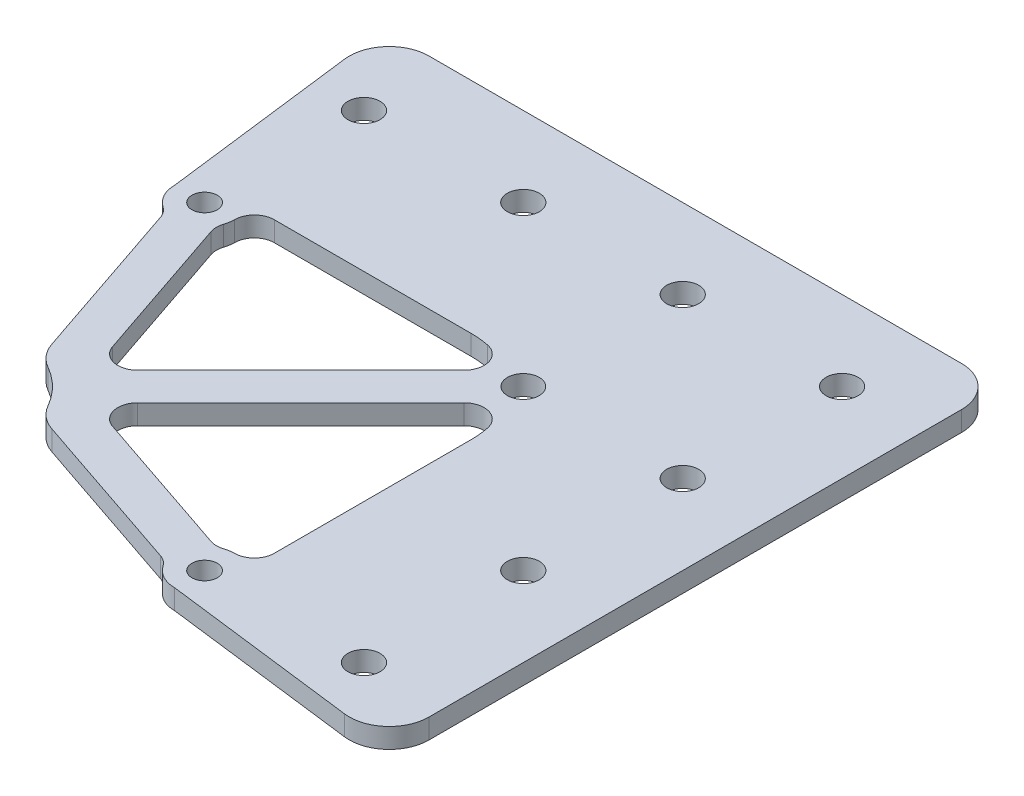
SolidWorks part; units mm, degrees
ref_plane "Front" through (0, 0, 0) normal (0, 0, 1) x (1, 0, 0)
ref_plane "Top" through (0, 0, 0) normal (0, 1, 0) x (1, 0, 0)
ref_plane "Right" through (0, 0, 0) normal (1, 0, 0) x (0, 0, -1)
sketch "Sketch1" plane through (0, 0, 0) normal (0, 1, 0) x (1, 0, 0)
  line L1 (-63.5, 63.5) -> (63.5, 63.5)
  line L2 (-63.5, 63.5) -> (-63.5, -63.5)
  line L3 (-63.5, -63.5) -> (63.5, -63.5)
  line L4 (63.5, 63.5) -> (63.5, -63.5)
  point P4 (39.9494, -25.0788)
  point P5 (0, 63.5)
  point P7 (-63.5, 0)
  point P8 (-38.1, 27.9109)
  dimension "D1" = 127
  dimension "D2" = 127
extrude "Boss-Extrude 1" add sketch "Sketch1" along normal blind 3.175
sketch "Sketch5" plane through (0, 0, 0) normal (0, -1, 0) x (1, 0, 0)
  line L0 (-30.1625, -25.4) -> (-34.925, -63.5)
  line L8 (-34.925, -63.5) -> (-63.5, -63.5)
  line L11 (-63.5, -63.5) -> (-63.5, 63.5)
  line L23 (25.4, 30.1625) -> (63.5, 34.925)
  line L27 (-38.3869, -28.575) -> (-33.3375, -28.575)
  line L28 (-26.8812, -19.8711) -> (-20.4899, -0.9811)
  line L29 (-34.3097, 4.4018) -> (-36.3512, 2.183)
  line L31 (-26.8812, -19.8711) -> (-20.4899, -0.9811)
  line L59 (-63.5, 63.5) -> (63.5, 63.5)
  line L64 (63.5, 63.5) -> (63.5, 34.925)
  line L73 (18.4349, -22.9251) -> (-7.5737, 3.0836)
  line L74 (-12.8263, 1.8561) -> (-20.8661, -21.9063)
  line L75 (-17.4625, -28.575) -> (13.9023, -28.575)
  line L76 (18.4349, -22.9251) -> (-7.5737, 3.0836)
  line L77 (-12.8263, 1.8561) -> (-20.8661, -21.9063)
  line L78 (-17.4625, -28.575) -> (13.9023, -28.575)
  line L88 (63.5, 63.5) -> (63.5, -63.5) construction
  line L89 (63.5, -63.5) -> (-63.5, -63.5) construction
  line L109 (28.575, -13.9023) -> (28.575, 17.4625)
  line L110 (21.9063, 20.8661) -> (-1.8561, 12.8263)
  line L111 (-3.0836, 7.5737) -> (22.9251, -18.4349)
  line L112 (28.575, -13.9023) -> (28.575, 17.4625)
  line L113 (21.9063, 20.8661) -> (-1.8561, 12.8263)
  line L114 (-3.0836, 7.5737) -> (22.9251, -18.4349)
  line L116 (0.9811, 20.4899) -> (19.8711, 26.8812)
  line L117 (28.575, 33.3375) -> (28.575, 44.3244)
  line L118 (25.4, 47.4994) -> (13.9965, 47.4994)
  line L119 (-1.9502, 36.2794) -> (-4.2984, 34.1559)
  line L120 (0.9811, 20.4899) -> (19.8711, 26.8812)
  line L126 (-20.4899, -0.9811) -> (-17.1581, 8.8661)
  line L127 (0.9811, 20.4899) -> (-8.8661, 17.1581)
  arc A69 (-41.0199, -7.9307) -> (-43.8396, -12.1698) centre (-40.8498, -11.1011) ccw
  arc A70 (-43.3218, -21.0917) -> (-43.8396, -12.1698) centre (-58.7883, -17.5133) ccw
  arc A71 (-43.3218, -21.0917) -> (-42.5927, -23.9267) centre (-40.2285, -21.8074) ccw
  arc A72 (-41.4877, -26.0822) -> (-42.5927, -23.9267) centre (-46.139, -27.1056) ccw
  arc A73 (-41.4877, -26.0822) -> (-38.3869, -28.575) centre (-38.3869, -25.4) ccw
  arc A74 (-33.3375, -28.575) -> (-30.1625, -25.4) centre (-33.3375, -25.4) ccw
  arc A75 (-28.0932, -21.4721) -> (-30.1625, -25.4) centre (-25.4, -25.4) ccw
  arc A76 (-28.0932, -21.4721) -> (-26.8812, -19.8711) centre (-29.8887, -18.8536) ccw
  arc A77 (-20.4899, -0.9811) -> (-23.3156, 3.2062) centre (-23.4974, 0.0365) ccw
  arc A78 (-30.5807, 5.1053) -> (-23.3156, 3.2062) centre (-22.225, 22.225) ccw
  arc A79 (-30.5807, 5.1053) -> (-34.3097, 4.4018) centre (-31.9733, 2.252) ccw
  arc A80 (-36.3512, 2.183) -> (-36.9188, -1.2501) centre (-34.0147, 0.0332) ccw
  arc A81 (-41.0199, -7.9307) -> (-36.9188, -1.2501) centre (-41.275, -3.175) ccw
  arc A88 (-28.0932, -21.4721) -> (-30.1625, -25.4) centre (-25.4, -25.4) ccw
  arc A89 (-28.0932, -21.4721) -> (-26.8812, -19.8711) centre (-29.8887, -18.8536) ccw
  arc A274 (25.4, -23.3807) -> (25.4, -27.4193) centre (25.4, -25.4) ccw
  arc A275 (25.4, -27.4193) -> (25.4, -23.3807) centre (25.4, -25.4) ccw
  arc A276 (25.4, -23.3807) -> (25.4, -27.4193) centre (25.4, -25.4) ccw construction
  arc A277 (25.4, -27.4193) -> (25.4, -23.3807) centre (25.4, -25.4) ccw construction
  arc A298 (-22.225, 7.9375) -> (-22.225, 36.5125) centre (-22.225, 22.225) ccw
  arc A299 (-22.225, 36.5125) -> (-22.225, 7.9375) centre (-22.225, 22.225) ccw
  arc A300 (-17.1581, 8.8661) -> (-8.8661, 17.1581) centre (-22.225, 22.225) ccw
  arc A313 (-25.4, -23.3807) -> (-25.4, -27.4193) centre (-25.4, -25.4) ccw construction
  arc A314 (25.4, 27.4193) -> (25.4, 23.3807) centre (25.4, 25.4) ccw construction
  arc A315 (13.9023, -28.575) -> (16.8216, -28.2817) centre (13.9023, -13.9023) ccw
  arc A316 (16.8216, -28.2817) -> (18.4349, -22.9251) centre (16.1899, -25.1701) ccw
  arc A317 (-7.5737, 3.0836) -> (-9.8188, 4.0135) centre (-9.8188, 0.8385) ccw
  arc A318 (-9.8188, 4.0135) -> (-12.8263, 1.8561) centre (-9.8188, 0.8385) ccw
  arc A319 (-20.8661, -21.9063) -> (-20.8752, -23.9143) centre (-17.8586, -22.9239) ccw
  arc A320 (-20.6375, -25.4) -> (-20.8752, -23.9143) centre (-25.4, -25.4) ccw
  arc A321 (-20.6375, -25.4) -> (-17.4625, -28.575) centre (-17.4625, -25.4) ccw
  arc A322 (13.9023, -28.575) -> (16.8216, -28.2817) centre (13.9023, -13.9023) ccw
  arc A323 (16.8216, -28.2817) -> (18.4349, -22.9251) centre (16.1899, -25.1701) ccw
  arc A324 (-7.5737, 3.0836) -> (-9.8188, 4.0135) centre (-9.8188, 0.8385) ccw
  arc A325 (-9.8188, 4.0135) -> (-12.8263, 1.8561) centre (-9.8188, 0.8385) ccw
  arc A326 (-20.8661, -21.9063) -> (-20.8752, -23.9143) centre (-17.8586, -22.9239) ccw
  arc A327 (-20.6375, -25.4) -> (-20.8752, -23.9143) centre (-25.4, -25.4) ccw
  arc A328 (-20.6375, -25.4) -> (-17.4625, -28.575) centre (-17.4625, -25.4) ccw
  arc A329 (28.2817, -16.8216) -> (28.575, -13.9023) centre (13.9023, -13.9023) ccw
  arc A330 (28.575, 17.4625) -> (25.4, 20.6375) centre (25.4, 17.4625) ccw
  arc A331 (23.9143, 20.8752) -> (25.4, 20.6375) centre (25.4, 25.4) ccw
  arc A332 (23.9143, 20.8752) -> (21.9063, 20.8661) centre (22.9239, 17.8586) ccw
  arc A333 (-1.8561, 12.8263) -> (-3.0836, 7.5737) centre (-0.8385, 9.8188) ccw
  arc A454 (22.9251, -18.4349) -> (25.1701, -19.3649) centre (25.1701, -16.1899) ccw
  arc A455 (25.1701, -19.3649) -> (28.2817, -16.8216) centre (25.1701, -16.1899) ccw
  arc A456 (28.2817, -16.8216) -> (28.575, -13.9023) centre (13.9023, -13.9023) ccw
  arc A457 (28.575, 17.4625) -> (25.4, 20.6375) centre (25.4, 17.4625) ccw
  arc A458 (23.9143, 20.8752) -> (25.4, 20.6375) centre (25.4, 25.4) ccw
  arc A459 (23.9143, 20.8752) -> (21.9063, 20.8661) centre (22.9239, 17.8586) ccw
  arc A460 (-1.8561, 12.8263) -> (-3.0836, 7.5737) centre (-0.8385, 9.8188) ccw
  arc A461 (22.9251, -18.4349) -> (25.1701, -19.3649) centre (25.1701, -16.1899) ccw
  arc A462 (25.1701, -19.3649) -> (28.2817, -16.8216) centre (25.1701, -16.1899) ccw
  arc A470 (19.8711, 26.8812) -> (21.4721, 28.0932) centre (18.8536, 29.8887) ccw
  arc A471 (25.4, 30.1625) -> (21.4721, 28.0932) centre (25.4, 25.4) ccw
  arc A472 (25.4, 30.1625) -> (28.575, 33.3375) centre (25.4, 33.3375) ccw
  arc A473 (28.575, 44.3244) -> (25.4, 47.4994) centre (25.4, 44.3244) ccw
  arc A474 (13.9965, 47.4994) -> (12.0915, 46.8644) centre (13.9965, 44.3244) ccw
  arc A475 (10.2574, 46.0231) -> (12.0915, 46.8644) centre (9.234, 50.6744) ccw
  arc A476 (10.2574, 46.0231) -> (7.8338, 42.2634) centre (10.9397, 42.9223) ccw
  arc A477 (3.175, 36.5125) -> (7.8338, 42.2634) centre (3.175, 41.275) ccw
  arc A478 (1.3776, 36.8647) -> (3.175, 36.5125) centre (3.175, 41.275) ccw
  arc A479 (1.3776, 36.8647) -> (-1.9502, 36.2794) centre (0.1793, 33.9245) ccw
  arc A480 (-4.2984, 34.1559) -> (-5.034, 30.433) centre (-2.1688, 31.801) ccw
  arc A481 (-3.2062, 23.3156) -> (-5.034, 30.433) centre (-22.225, 22.225) ccw
  arc A482 (-3.2062, 23.3156) -> (-0.0365, 20.3224) centre (-0.0365, 23.4974) ccw
  arc A483 (-0.0365, 20.3224) -> (0.9811, 20.4899) centre (-0.0365, 23.4974) ccw
  arc A484 (19.8711, 26.8812) -> (21.4721, 28.0932) centre (18.8536, 29.8887) ccw
  arc A485 (25.4, 30.1625) -> (21.4721, 28.0932) centre (25.4, 25.4) ccw
  arc A555 (-25.4, -23.3807) -> (-25.4, -27.4193) centre (-25.4, -25.4) ccw
  arc A556 (25.4, 27.4193) -> (25.4, 23.3807) centre (25.4, 25.4) ccw
  circle A561 centre (25.4, -25.4) radius 2.5273
  arc A566 (-25.4, -23.3807) -> (-25.4, -27.4193) centre (-25.4, -25.4) cw
  arc A567 (25.4, 27.4193) -> (25.4, 23.3807) centre (25.4, 25.4) cw
  dimension "D1" = 0.508
  dimension "D5" = 98.425
  dimension "D6" = 98.425
  dimension "D4" = 0
  dimension "D23" = 0
  dimension "D29" = 0
  dimension "D32" = 0
  dimension "D37" = 0
  dimension "D38" = 0
extrude "Cut-Extrude1" cut sketch "Sketch5" against normal through all
fillet "Fillet1" radius 6.35 1 edges at (63.5, 1.5875, -63.5)
fillet "Fillet2" radius 6.35 2 edges at (-34.925, 1.5875, -63.5) (63.5, 1.5875, 34.925)
fillet "Fillet3" radius 6.35 2 edges at (-8.8661, 1.5875, 17.1581) (-17.1581, 1.5875, 8.8661)
hole_wizard "#10 Clearance Hole1" positions "Sketch8" profile "Sketch9" hole size "#10" standard "ANSI Inch"
sketch "Sketch8" plane through (0, 0, 0) normal (0, -1, 0) x (-1, 0, 0)
  point P1 (-50.8, 50.8)
  point P4 (-25.4, 50.8)
  point P9 (38.1, 50.8)
  point P12 (50.8, 50.8)
  point P21 (0, 50.8)
  point P26 (76.2, 50.8)
  point P31 (25.4, 50.8)
  point P35 (-50.8, 25.4)
  point P38 (-50.8, 0)
  point P41 (-50.8, -25.4)
  point P44 (-50.8, -50.8)
  point P48 (-50.8, -76.2)
sketch "Sketch9" plane through (50.8, 0, -50.8) normal (1, 0, 0) x (0, 0, -1)
  line L0 (0, 0) -> (0, 11.4398)
  line L1 (0, 11.4398) -> (2.5527, 9.906)
  line L2 (2.5527, 9.906) -> (2.5527, 0)
  line L5 (2.5527, 0) -> (0, 0)
  line L10 (0, 11.4398) -> (-2.5527, 9.906) construction
  line L11 (0, -6.35) -> (0, 107.95) construction
  dimension "Hole Dia." = 5.1054
  dimension "Hole Depth" = 9.906
  dimension "Drill Angle" = 118
